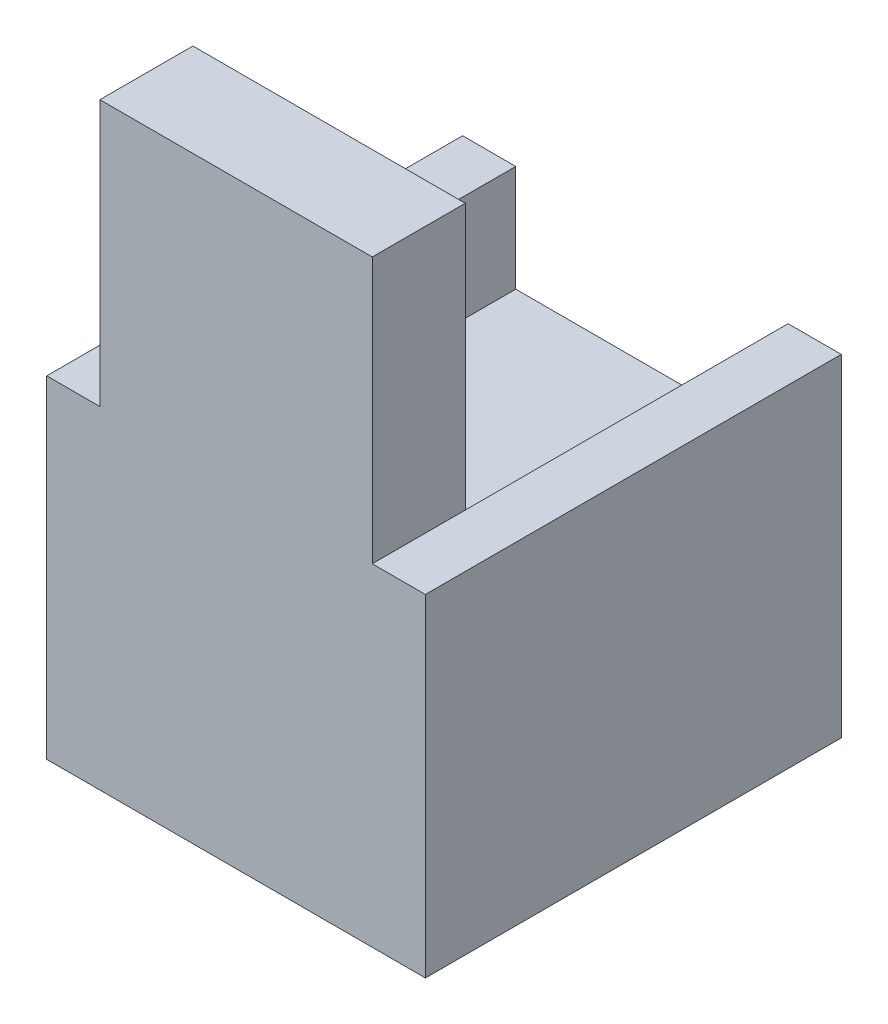
SolidWorks part; units mm, degrees
ref_plane "Front Plane" through (0, 0, 0) normal (0, 0, 1) x (1, 0, 0)
ref_plane "Top Plane" through (0, 0, 0) normal (0, 1, 0) x (1, 0, 0)
ref_plane "Right Plane" through (0, 0, 0) normal (1, 0, 0) x (0, 0, -1)
sketch "Sketch1" plane through (0, 0, 0) normal (0, 1, 0) x (1, 0, 0)
  line L1 (-395.8039, 0) -> (328.0961, 0)
  line L2 (-395.8039, 0) -> (-395.8039, -795.02)
  line L3 (-395.8039, -795.02) -> (328.0961, -795.02)
  line L4 (328.0961, 0) -> (328.0961, -795.02)
  dimension "D1" = 795.02
  dimension "D2" = 723.9
extrude "Boss-Extrude1" add sketch "Sketch1" along normal blind 431.8
sketch "Sketch2" plane through (0, 431.8, 0) normal (0, 1, 0) x (1, 0, 0)
  line L0 (-395.8039, -795.02) -> (328.0961, -795.02) construction
  line L1 (-395.8039, 0) -> (-294.2039, 0)
  line L2 (-395.8039, 0) -> (-395.8039, -795.02)
  line L3 (-395.8039, -795.02) -> (-294.2039, -795.02)
  line L4 (-294.2039, 0) -> (-294.2039, -795.02)
  line L6 (328.0961, 0) -> (226.4961, 0)
  line L7 (328.0961, 0) -> (328.0961, -795.02)
  line L8 (328.0961, -795.02) -> (226.4961, -795.02)
  line L9 (226.4961, 0) -> (226.4961, -795.02)
  dimension "D1" = 101.6
extrude "Boss-Extrude2" add sketch "Sketch2" along normal blind 203.2
sketch "Sketch3" plane through (0, 431.8, 0) normal (0, 1, 0) x (1, 0, 0)
  line L0 (-294.2039, -795.02) -> (-294.2039, 0) construction
  line L1 (-294.2039, -617.22) -> (226.4961, -617.22)
  line L2 (-294.2039, -617.22) -> (-294.2039, -795.02)
  line L3 (-294.2039, -795.02) -> (226.4961, -795.02)
  line L4 (226.4961, -617.22) -> (226.4961, -795.02)
  dimension "D1" = 177.8
extrude "Boss-Extrude3" add sketch "Sketch3" along normal blind 711.2
